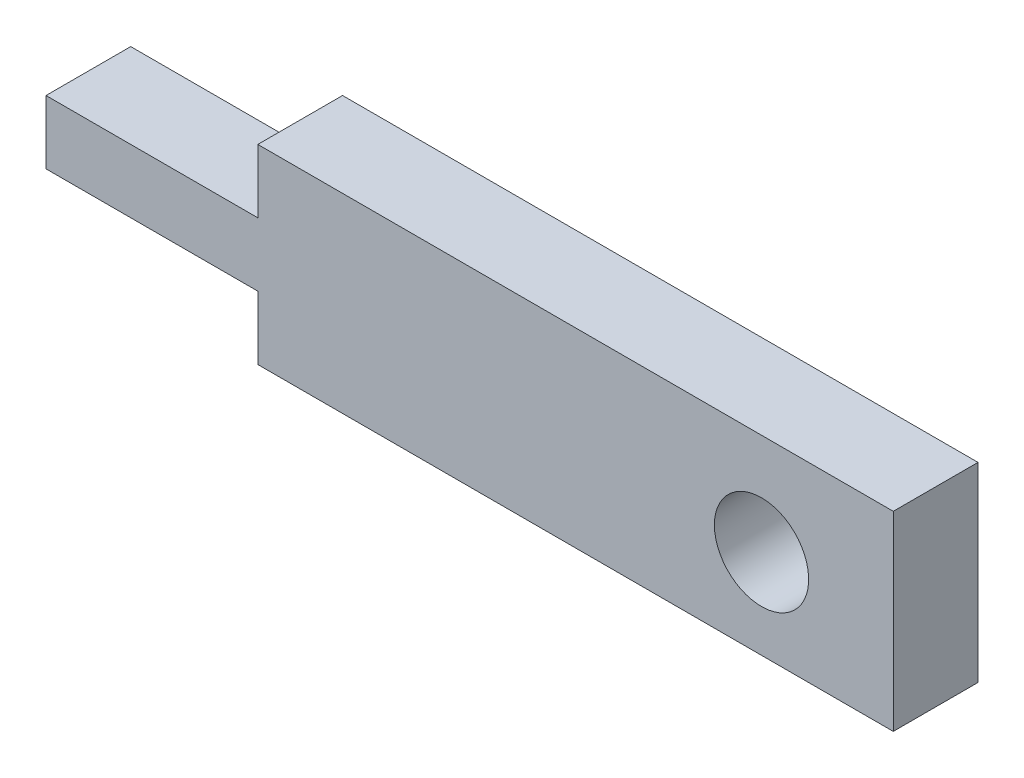
SolidWorks part; units mm, degrees
ref_plane "Alzado" through (0, 0, 0) normal (0, 0, 1) x (1, 0, 0)
ref_plane "Planta" through (0, 0, 0) normal (0, 1, 0) x (1, 0, 0)
ref_plane "Vista lateral" through (0, 0, 0) normal (1, 0, 0) x (0, 0, -1)
sketch "Croquis1" plane through (0, 0, 0) normal (0, 1, 0) x (1, 0, 0)
  line L1 (-175, -10) -> (175, -10)
  line L2 (-175, -10) -> (-175, 10)
  line L3 (-175, 10) -> (175, 10)
  line L4 (175, -10) -> (175, 10)
  line L5 (-175, -10) -> (175, 10) construction
  line L6 (-175, 10) -> (175, -10) construction
  point P0 (0, 0)
  dimension "D1" = 350
  dimension "D2" = 20
extrude "Saliente-Extruir1" add sketch "Croquis1" along normal blind 45
sketch "Croquis2" plane through (0, 0, -10) normal (0, 0, -1) x (-1, 0, 0)
  line L0 (-175, 0) -> (175, 0) construction
  line L1 (-165, 0) -> (-122.8, 0)
  line L2 (-165, 0) -> (-165, 42.2)
  line L3 (-165, 42.2) -> (-122.8, 42.2)
  line L4 (-122.8, 0) -> (-122.8, 42.2)
  line L5 (-175, 45) -> (-175, 0) construction
  line L6 (-165, 42.2) -> (-122.8, 0) construction
  circle A0 centre (-143.9, 21.1) radius 11.125
  dimension "D4" = 22.25
  dimension "D1" = 10
  dimension "D2" = 42.2
  dimension "D3" = 42.2
extrude "Cortar-Extruir1" cut sketch "Croquis2" against normal through all contours A0
mirror "Simetría1" about plane through (0, 0, 0) normal (1, 0, 0) of "Cortar-Extruir1"
sketch "Croquis3" plane through (0, 0, 10) normal (0, 0, 1) x (1, 0, 0)
  line L0 (0, 0) -> (25, 0)
  line L1 (-175, 0) -> (175, 0) construction
  line L2 (25, 0) -> (25, 15)
  line L3 (25, 15) -> (-25, 15)
  line L4 (-25, 15) -> (-25, 30)
  line L5 (-25, 30) -> (25, 30)
  line L6 (25, 30) -> (25, 45)
  line L7 (-175, 45) -> (175, 45) construction
  line L13 (-175, 0) -> (175, 0)
  line L14 (175, 0) -> (175, 45)
  line L15 (175, 45) -> (-175, 45)
  line L16 (-175, 45) -> (-175, 0)
  line L17 (-175, 0) -> (175, 0)
  line L18 (175, 0) -> (175, 45)
  line L19 (175, 45) -> (-175, 45)
  line L20 (-175, 45) -> (-175, 0)
  point P5 (-25, 22.5)
  circle M8 centre (-143.9, 21.1) radius 11.125
  line M10 (-175, 0) -> (175, 0)
  line M12 (175, 45) -> (-175, 45)
  line M13 (-175, 45) -> (-175, 0)
  dimension "D1" = 15
  dimension "D2" = 15
  dimension "D3" = 25
  dimension "D4" = 50
  dimension "D5" = 50
  dimension "D6" = 0
extrude "Cortar-Extruir3" cut sketch "Croquis3" against normal through all contours L5 L6 L2 L3 L4 M12 M13 M10 M8
